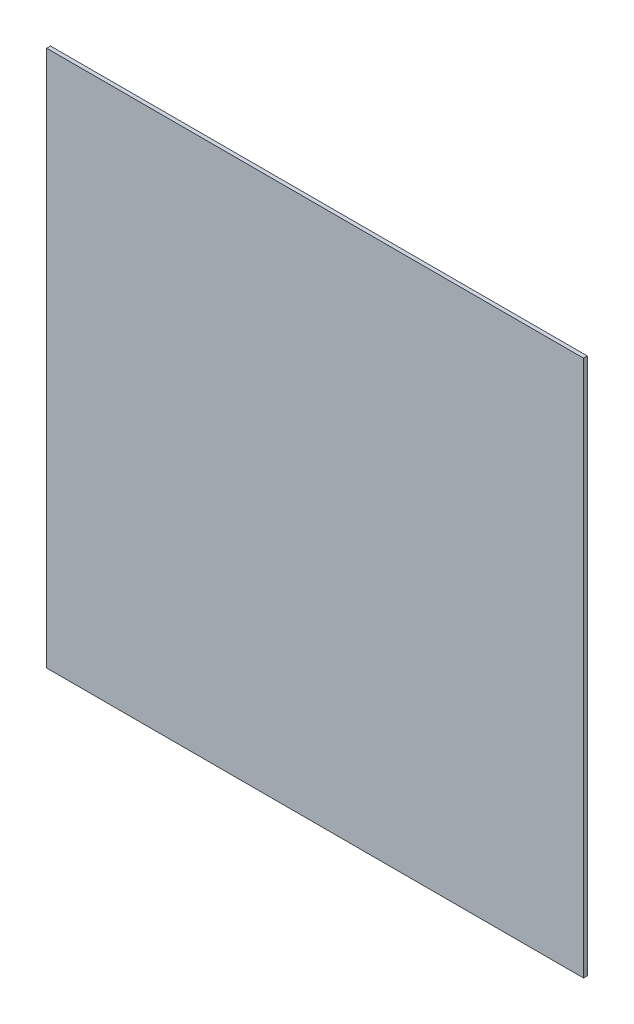
SolidWorks part; units mm, degrees
ref_plane "前视基准面" through (0, 0, 0) normal (0, 0, 1) x (1, 0, 0)
ref_plane "上视基准面" through (0, 0, 0) normal (0, 1, 0) x (1, 0, 0)
ref_plane "右视基准面" through (0, 0, 0) normal (1, 0, 0) x (0, 0, -1)
sketch "草图1" plane through (0, 0, 0) normal (0, 0, 1) x (1, 0, 0)
  line L1 (-210, -210) -> (210, -210)
  line L2 (-210, -210) -> (-210, 210)
  line L3 (-210, 210) -> (210, 210)
  line L4 (210, -210) -> (210, 210)
  line L5 (-210, -210) -> (210, 210) construction
  line L6 (-210, 210) -> (210, -210) construction
  point P0 (0, 0)
  dimension "D1" = 420
  dimension "D2" = 420
extrude "凸台-拉伸1" add sketch "草图1" along normal blind 3
